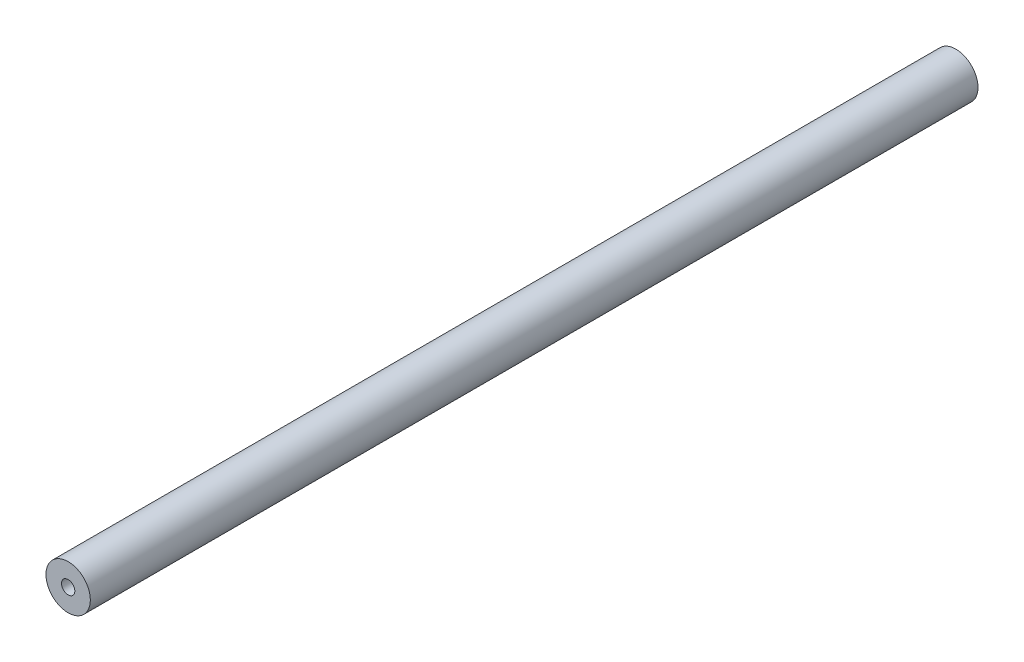
SolidWorks part; units mm, degrees
ref_plane "Front Plane" through (0, 0, 0) normal (0, 0, 1) x (1, 0, 0)
ref_plane "Top Plane" through (0, 0, 0) normal (0, 1, 0) x (1, 0, 0)
ref_plane "Right Plane" through (0, 0, 0) normal (1, 0, 0) x (0, 0, -1)
sketch "Sketch1" plane through (0, 0, 0) normal (0, 0, 1) x (1, 0, 0)
  circle A0 centre (0, 0) radius 10
  dimension "D1" = 20
extrude "Boss-Extrude1" add sketch "Sketch1" along normal blind 400
sketch "Sketch2" plane through (0, 0, 400) normal (0, 0, 1) x (1, 0, 0)
  circle A0 centre (0, 0) radius 3
  dimension "D1" = 6
extrude "Cut-Extrude1" cut sketch "Sketch2" against normal blind 20
sketch "Sketch3" plane through (0, 0, 0) normal (0, 0, -1) x (-1, 0, 0)
  circle A0 centre (0, 0) radius 3
  dimension "D1" = 6
extrude "Cut-Extrude2" cut sketch "Sketch3" against normal blind 20
